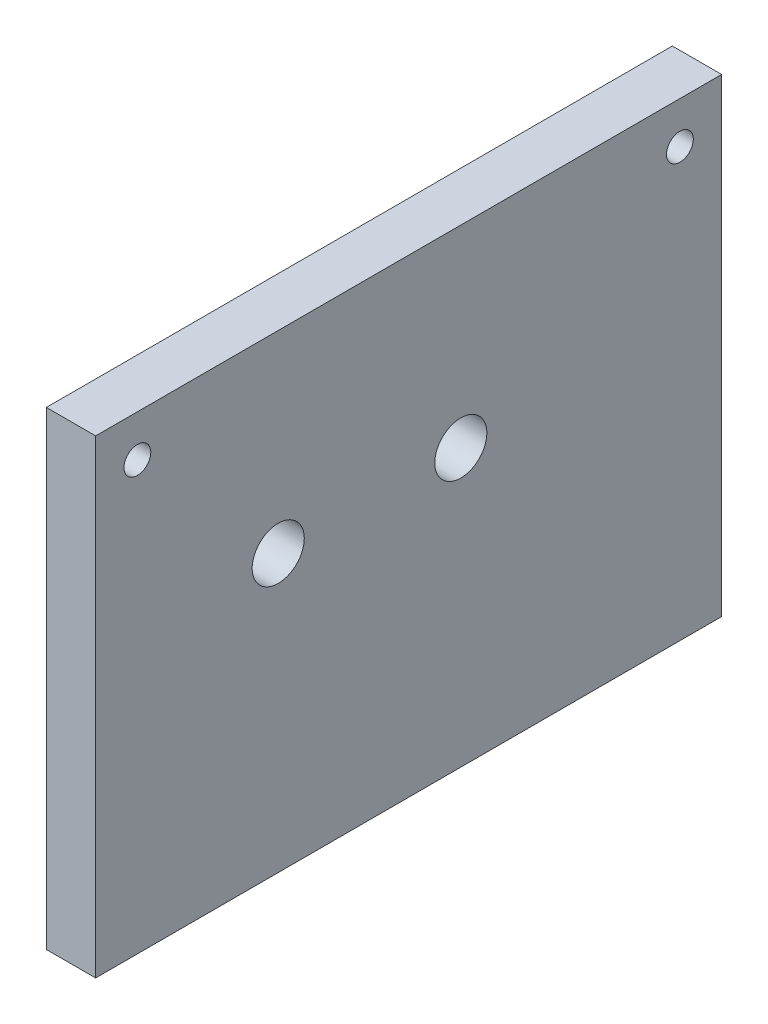
SolidWorks part; units mm, degrees
ref_plane "Front Plane" through (0, 0, 0) normal (0, 0, 1) x (1, 0, 0)
ref_plane "Top Plane" through (0, 0, 0) normal (0, 1, 0) x (1, 0, 0)
ref_plane "Right Plane" through (0, 0, 0) normal (1, 0, 0) x (0, 0, -1)
sketch "Sketch1" plane through (0, 0, 0) normal (1, 0, 0) x (0, 0, -1)
  line L0 (-66.04, 46.99) -> (66.04, 46.99) construction
  line L1 (-76.2, 57.15) -> (76.2, 57.15)
  line L2 (-76.2, 57.15) -> (-76.2, -57.15)
  line L3 (-76.2, -57.15) -> (76.2, -57.15)
  line L4 (76.2, 57.15) -> (76.2, -57.15)
  line L5 (-76.2, 57.15) -> (76.2, -57.15) construction
  line L6 (-76.2, -57.15) -> (76.2, 57.15) construction
  line L7 (-76.2, -54.04) -> (76.2, -54.04) construction
  line L8 (-76.2, -54.04) -> (-76.2, -66.04) construction
  line L9 (-76.2, -66.04) -> (76.2, -66.04) construction
  line L10 (76.2, -54.04) -> (76.2, -66.04) construction
  circle A2 centre (-31.75, 10.16) radius 6.3436
  circle A3 centre (-31.75, 10.16) radius 32.8422 construction
  circle A4 centre (12.7, 10.16) radius 6.3437
  circle A5 centre (12.7, 10.16) radius 32.8422 construction
  circle A6 centre (-31.75, 10.16) radius 13.7287 construction
  circle A7 centre (12.7, 10.16) radius 13.7287 construction
  point P0 (0, 0)
  point P20 (0, 46.99)
  point P21 (0, 0)
  dimension "D4" = 76.2
  dimension "D5" = 65.6844
  dimension "D8" = 27.4574
  dimension "D9" = 12.6873
  dimension "D11" = 10.16
  dimension "D1" = 152.4
  dimension "D2" = 114.3
  dimension "D3" = 12
  dimension "D6" = 67.31
  dimension "D7" = 44.45
  dimension "D10" = 63.5
  dimension "D12" = 10.16
extrude "Boss-Extrude1" add sketch "Sketch1" along normal blind 12
sketch "Sketch2" plane through (0, -57.15, 0) normal (0, -1, 0) x (1, 0, 0)
  line L0 (6, -66.675) -> (6, 66.675) construction
  line L1 (12, 76.2) -> (0, 76.2) construction
  line L2 (12, -76.2) -> (0, -76.2) construction
  point P2 (0, 0)
  point P4 (6, 0)
  point P9 (6, -76.2)
  point P10 (0, 0)
  point P11 (57.9749, 66.675)
  point P14 (0, 0)
  dimension "D1" = 9.525
hole_wizard "Tap Drill for #10-32 Tap1" positions "Sketch3" profile "Sketch4" hole size "#10-32" standard "ANSI Inch"
sketch "Sketch3" plane through (0, -57.15, 0) normal (0, -1, 0) x (-1, 0, 0)
  point P0 (-6, -66.675)
  point P3 (-6, 0)
  point P6 (-6, 66.675)
sketch "Sketch4" plane through (6, -57.15, 66.675) normal (1, 0, 0) x (0, 0, -1)
  line L0 (0, 0) -> (0, 13.9133)
  line L1 (0, 13.9133) -> (2.0193, 12.7)
  line L2 (2.0193, 12.7) -> (2.0193, 0)
  line L5 (2.0193, 0) -> (0, 0)
  line L10 (0, 13.9133) -> (-2.0193, 12.7) construction
  line L11 (0, -6.35) -> (0, 107.95) construction
  dimension "Hole Dia." = 4.0386
  dimension "Hole Depth" = 12.7
  dimension "Drill Angle" = 118
hole_wizard "1/4 Clearance Hole1" positions "Sketch5" profile "Sketch6" hole size "1/4" standard "ANSI Inch"
sketch "Sketch5" plane through (0, 0, 0) normal (-1, 0, 0) x (0, 0, 1)
  point P0 (-66.04, 46.99)
  point P3 (66.04, 46.99)
sketch "Sketch6" plane through (0, 46.99, -66.04) normal (0, 1, 0) x (0, 0, 1)
  line L0 (0, 0) -> (0, 14.6611)
  line L1 (0, 14.6611) -> (3.2639, 12.7)
  line L2 (3.2639, 12.7) -> (3.2639, 0)
  line L5 (3.2639, 0) -> (0, 0)
  line L10 (0, 14.6611) -> (-3.2639, 12.7) construction
  line L11 (0, -6.35) -> (0, 107.95) construction
  dimension "Hole Dia." = 6.5278
  dimension "Hole Depth" = 12.7
  dimension "Drill Angle" = 118
